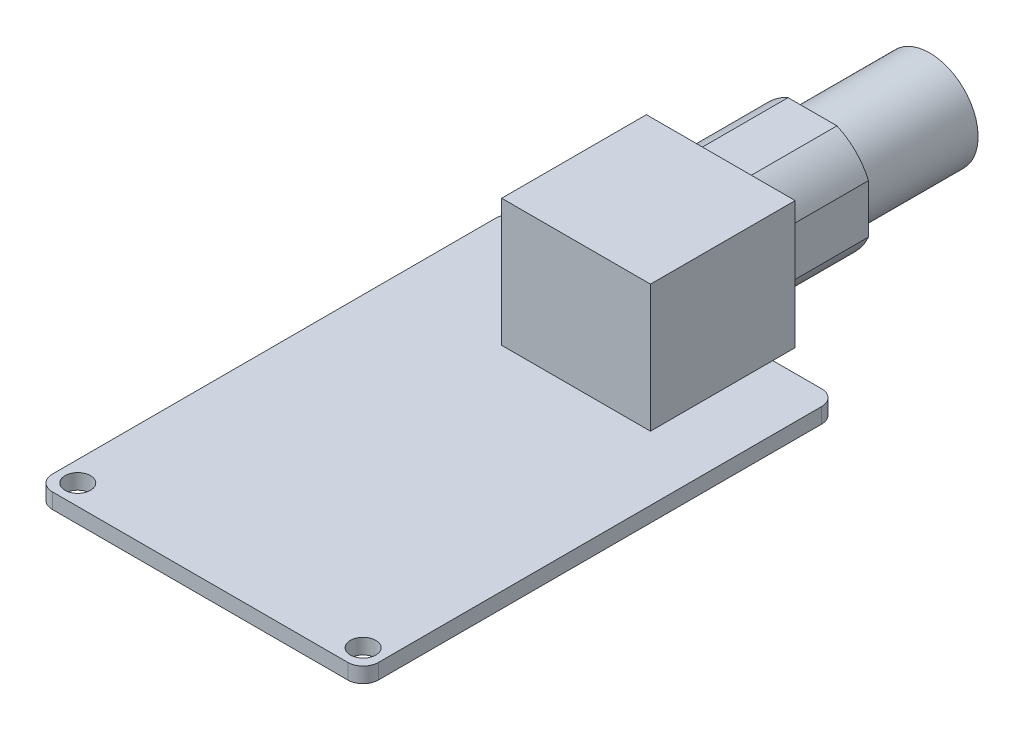
SolidWorks part; units mm, degrees
ref_plane "前基準面" through (0, 0, 0) normal (0, 0, 1) x (1, 0, 0)
ref_plane "上基準面" through (0, 0, 0) normal (0, 1, 0) x (1, 0, 0)
ref_plane "右基準面" through (0, 0, 0) normal (1, 0, 0) x (0, 0, -1)
sketch "草圖1" plane through (0, 0, 0) normal (0, 0, 1) x (1, 0, 0)
  line L0 (-101.7064, 41) -> (-14.1064, 41) construction
  line L2 (-12.0331, 2) -> (-12.0331, 43) construction
  circle A0 centre (-29.3409, 31.5) radius 6
  dimension "D1" = 12
  dimension "D3" = 17.3078
  dimension "D2" = 9.5
extrude "填料-伸長1" add sketch "草圖1" against normal blind 5.5 and the other way blind 3.5
sketch "草圖2" plane through (0, 0, -5.5) normal (0, 0, -1) x (-1, 0, 0)
  circle A0 centre (29.3409, 31.5) radius 4.75
  circle A1 centre (29.3409, 31.5) radius 6 construction
  dimension "D1" = 0
extrude "填料-伸長2" add sketch "草圖2" along normal blind 11.5
sketch "草圖3" plane through (0, 0, -17) normal (0, 0, -1) x (-1, 0, 0)
  circle A2 centre (29.3409, 31.5) radius 4.25
  circle A3 centre (29.3409, 31.5) radius 4.25
  dimension "D1" = 0.5
extrude "除料-伸長1" cut sketch "草圖3" against normal blind 11.5
sketch "草圖4" plane through (0, 0, 3.5) normal (0, 0, 1) x (1, 0, 0)
  line L1 (-36.6409, 37.6) -> (-22.0409, 37.6)
  line L2 (-36.6409, 37.6) -> (-36.6409, 25.1)
  line L3 (-36.6409, 25.1) -> (-22.0409, 25.1)
  line L4 (-22.0409, 37.6) -> (-22.0409, 25.1)
  circle A1 centre (-29.3409, 31.5) radius 6 construction
  point P6 (-22.0409, 31.35)
  dimension "D1" = 7.3
  dimension "D2" = 6.1
  dimension "D3" = 14.6
extrude "填料-伸長3" add sketch "草圖4" along normal blind 14.2
sketch "草圖5" plane through (0, 25.1, 0) normal (0, -1, 0) x (1, 0, 0)
  line L0 (-22.0409, 17.7) -> (-22.0409, 3.5) construction
  line L1 (-17.2409, 5.6974) -> (-46.2409, 5.6974)
  line L2 (-15.7409, 7.1974) -> (-15.7409, 50.6974)
  line L3 (-17.2409, 52.1974) -> (-46.2409, 52.1974)
  line L4 (-47.7409, 7.1974) -> (-47.7409, 50.6974)
  arc A0 (-15.7409, 50.6974) -> (-17.2409, 52.1974) centre (-17.2409, 50.6974) ccw
  arc A1 (-46.2409, 52.1974) -> (-47.7409, 50.6974) centre (-46.2409, 50.6974) ccw
  arc A2 (-46.2409, 5.6974) -> (-47.7409, 7.1974) centre (-46.2409, 7.1974) cw
  arc A3 (-17.2409, 5.6974) -> (-15.7409, 7.1974) centre (-17.2409, 7.1974) ccw
  circle A4 centre (-17.7409, 50.1974) radius 1.25
  circle A5 centre (-45.7409, 50.1974) radius 1.25
  point P8 (-15.7409, 52.1974)
  point P11 (-47.7409, 52.1974)
  point P14 (-47.7409, 5.6974)
  dimension "D4" = 1.5
  dimension "D5" = 2.5
  dimension "D6" = 2.5
  dimension "D7" = 2
  dimension "D8" = 2
  dimension "D9" = 2
  dimension "D10" = 2
  dimension "D1" = 32
  dimension "D2" = 46.5
  dimension "D3" = 6.3
extrude "填料-伸長4" add sketch "草圖5" along normal blind 1.5
sketch "草圖6" plane through (0, 0, -5.5) normal (0, 0, -1) x (-1, 0, 0)
  line L1 (26.943, 26) -> (31.7388, 26)
  line L2 (23.8409, 29.1021) -> (23.8409, 33.8979)
  line L3 (26.943, 37) -> (31.7388, 37)
  line L4 (34.8409, 29.1021) -> (34.8409, 33.8979)
  line L5 (23.8409, 26) -> (34.8409, 37) construction
  line L6 (23.8409, 37) -> (34.8409, 26) construction
  circle A0 centre (29.3409, 31.5) radius 6 construction
  arc A1 (34.8409, 29.1021) -> (34.8409, 33.8979) centre (29.3409, 31.5) ccw
  arc A2 (26.943, 26) -> (31.7388, 26) centre (29.3409, 31.5) ccw
  arc A3 (23.8409, 33.8979) -> (23.8409, 29.1021) centre (29.3409, 31.5) ccw
  arc A4 (31.7388, 37) -> (26.943, 37) centre (29.3409, 31.5) ccw
  point P0 (29.3409, 31.5)
  dimension "D1" = 11
  dimension "D2" = 11
extrude "除料-伸長2" cut sketch "草圖6" along direction (0, 0, 1) on the side against the normal up to surface (9 mm away)
